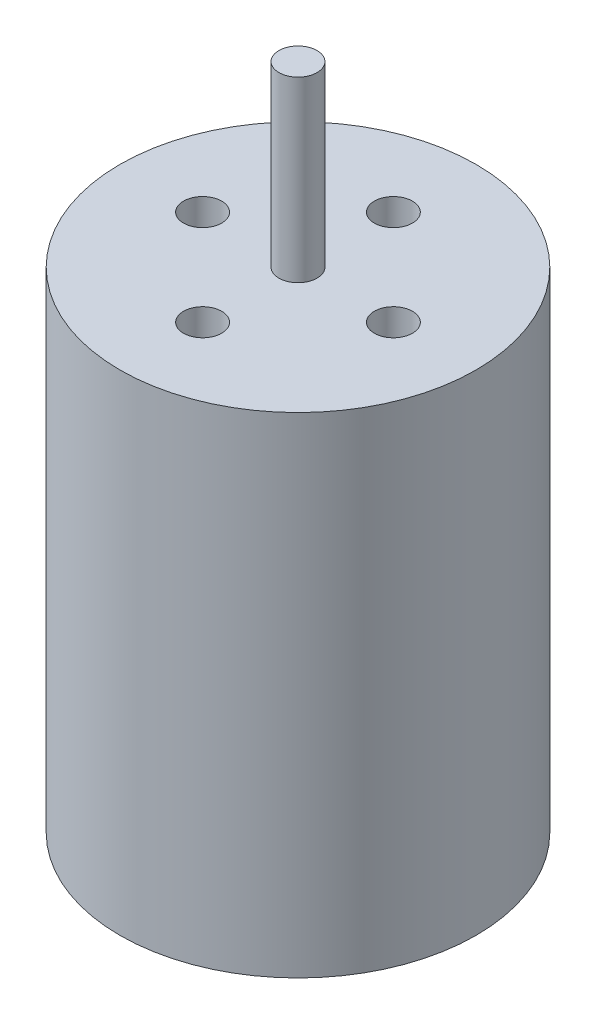
SolidWorks part; units mm, degrees
ref_plane "Front Plane" through (0, 0, 0) normal (0, 0, 1) x (1, 0, 0)
ref_plane "Top Plane" through (0, 0, 0) normal (0, 1, 0) x (1, 0, 0)
ref_plane "Right Plane" through (0, 0, 0) normal (1, 0, 0) x (0, 0, -1)
sketch "Sketch1" plane through (0, 0, 0) normal (0, 0, 1) x (1, 0, 0)
  line L0 (0, -23.4674) -> (0, 16.5224) construction
  line L1 (0, -27.5) -> (4.4, -27.5)
  line L2 (4.4, -27.5) -> (4.4, -25)
  line L3 (4.4, -25) -> (14, -25)
  line L4 (14, -25) -> (14, 13.5)
  line L5 (14, 13.5) -> (1.5, 13.5)
  line L6 (1.5, 13.5) -> (1.5, 27.5)
  line L7 (1.5, 27.5) -> (0, 27.5)
  line L8 (0, 27.5) -> (0, -27.5)
  dimension "D1" = 55
  dimension "D2" = 3
  dimension "D3" = 28
  dimension "D4" = 8.8
  dimension "D5" = 38.5
  dimension "D6" = 14
revolve "Revolve1" add sketch "Sketch1" angle 360 about L0
sketch "Sketch2" plane through (0, 13.5, 0) normal (0, 1, 0) x (1, 0, 0)
  line L0 (-7.5, 0) -> (0, -7.5) construction
  line L1 (-7.5, 0) -> (0, 7.5) construction
  line L2 (0, -7.5) -> (7.5, 0) construction
  line L3 (0, 7.5) -> (7.5, 0) construction
  line L4 (-7.5, 0) -> (7.5, 0) construction
  line L5 (0, -7.5) -> (0, 7.5) construction
  circle A0 centre (-7.5, 0) radius 1.5
  circle A1 centre (0, -7.5) radius 1.5
  circle A2 centre (7.5, 0) radius 1.5
  circle A3 centre (0, 7.5) radius 1.5
  point P1 (0, 0)
  dimension "D1" = 3
  dimension "D2" = 15
extrude "Cut-Extrude1" cut sketch "Sketch2" against normal blind 3
